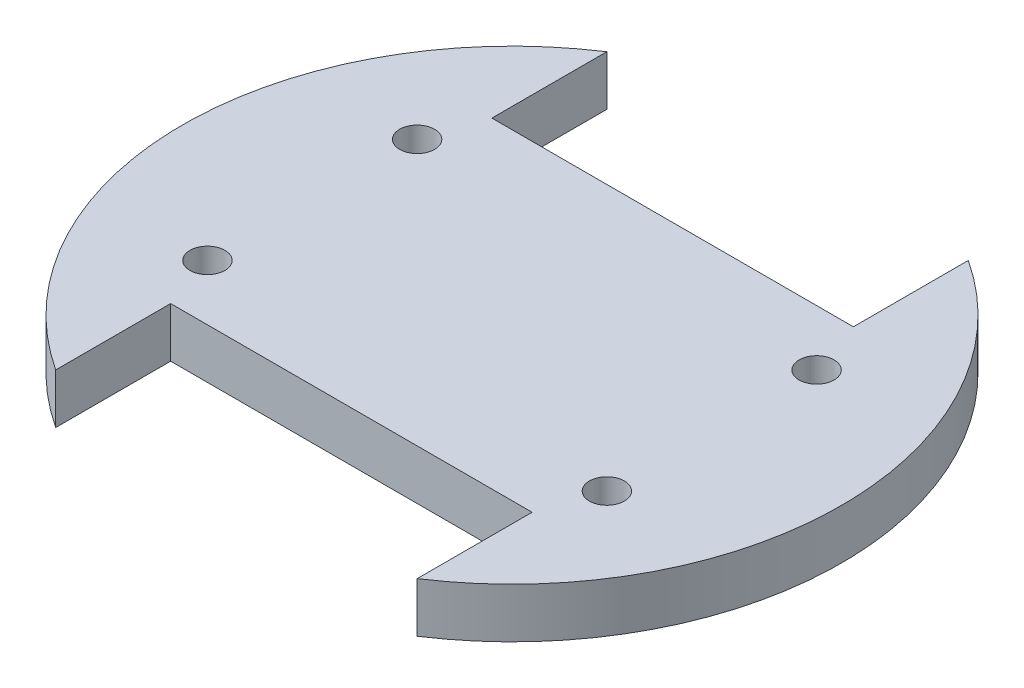
SolidWorks part; units mm, degrees
ref_plane "前视基准面" through (0, 0, 0) normal (0, 0, 1) x (1, 0, 0)
ref_plane "上视基准面" through (0, 0, 0) normal (0, 1, 0) x (1, 0, 0)
ref_plane "右视基准面" through (0, 0, 0) normal (1, 0, 0) x (0, 0, -1)
sketch "草图1" plane through (0, 0, 0) normal (0, 1, 0) x (1, 0, 0)
  circle A0 centre (0, 0) radius 33
  dimension "D1" = 66
extrude "凸台-拉伸1" add sketch "草图1" along normal blind 5
sketch "草图2" plane through (0, 5, 0) normal (0, 1, 0) x (1, 0, 0)
  line L0 (0, 31.3668) -> (0, -38.9806) construction
  line L1 (-18.0997, -44.9891) -> (18.0997, -44.9891)
  line L2 (-18.0997, -44.9891) -> (-18.0997, -16.0847)
  line L3 (-18.0997, -16.0847) -> (18.0997, -16.0847)
  line L4 (18.0997, -44.9891) -> (18.0997, -16.0847)
  line L5 (0, -16.0847) -> (0, -44.9891) construction
  line L6 (-18.0997, -30.5369) -> (18.0997, -30.5369) construction
  line L7 (18.0997, 16.0847) -> (-18.0997, 16.0847)
  line L8 (18.0997, 44.9891) -> (18.0997, 16.0847)
  line L9 (18.0997, 44.9891) -> (-18.0997, 44.9891)
  line L10 (-18.0997, 44.9891) -> (-18.0997, 16.0847)
  point P0 (0, -30.5369)
  point P7 (0, -16.0847)
  point P15 (0, 0)
extrude "切除-拉伸2" cut sketch "草图2" against normal through all
sketch "草图4" plane through (0, 5, 0) normal (0, 1, 0) x (1, 0, 0)
  line L0 (57.7787, 0) -> (-70.3131, 0) construction
  line L1 (0, 17.5568) -> (0, -25.1977) construction
  line L7 (0, 10.5) -> (0, -10.5) construction
  line L8 (-20, 0) -> (20, 0) construction
  circle A0 centre (-20, 10.5) radius 1.75
  circle A1 centre (20, 10.5) radius 1.75
  circle A2 centre (-20, -10.5) radius 1.75
  circle A3 centre (20, -10.5) radius 1.75
  point P3 (0, 0)
  dimension "D3" = 3.5
  dimension "D4" = 3.5
  dimension "D5" = 3.5
  dimension "D6" = 3.5
  dimension "D1" = 40
  dimension "D2" = 21
extrude "切除-拉伸3" cut sketch "草图4" against normal through all
